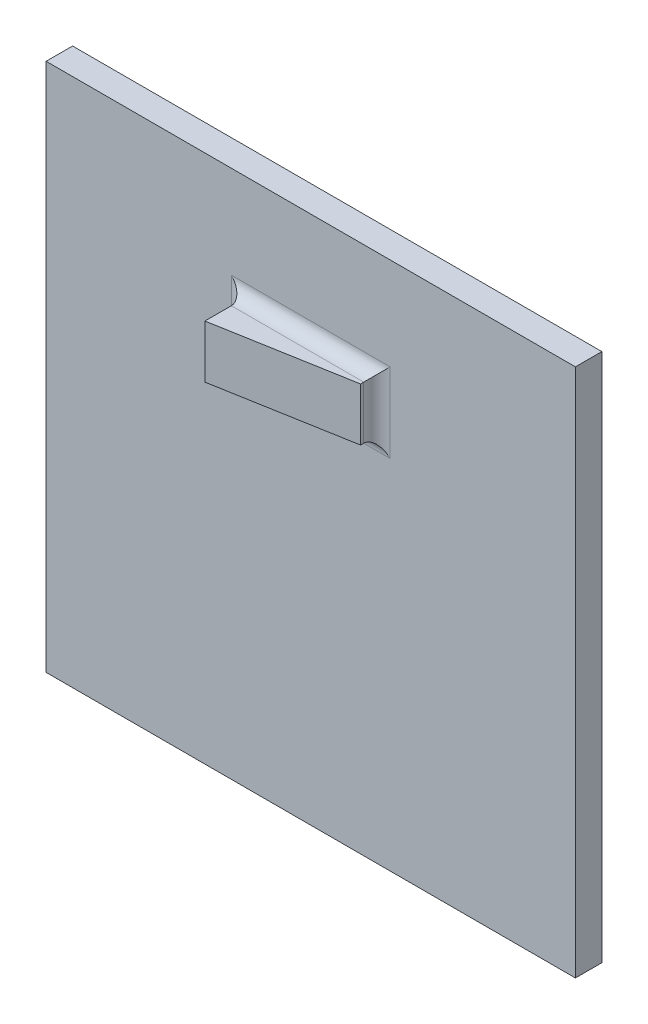
SolidWorks part; units mm, degrees
ref_plane "前视基准面" through (0, 0, 0) normal (0, 0, 1) x (1, 0, 0)
ref_plane "上视基准面" through (0, 0, 0) normal (0, 1, 0) x (1, 0, 0)
ref_plane "右视基准面" through (0, 0, 0) normal (1, 0, 0) x (0, 0, -1)
other "Configuration Table"
sketch "草图1" plane through (0, 0, 0) normal (0, 0, 1) x (1, 0, 0)
  line L1 (-20, 10) -> (20, 10)
  line L2 (-20, 10) -> (-20, -10)
  line L3 (-20, -10) -> (20, -10)
  line L4 (20, 10) -> (20, -10)
  line L5 (-20, 10) -> (20, -10) construction
  line L6 (-20, -10) -> (20, 10) construction
  point P0 (0, 0)
  dimension "D1" = 20
  dimension "D2" = 40
extrude "凸台-拉伸1" add sketch "草图1" along normal blind 2
sketch "草图2" plane through (0, 0, 2) normal (0, 0, 1) x (1, 0, 0)
  line L1 (-5, 2) -> (5, 2)
  line L2 (-5, 2) -> (-5, -2)
  line L3 (-5, -2) -> (5, -2)
  line L4 (5, 2) -> (5, -2)
  line L5 (-5, 2) -> (5, -2) construction
  line L6 (-5, -2) -> (5, 2) construction
  point P0 (0, 0)
  dimension "D1" = 4
  dimension "D2" = 10
extrude "凸台-拉伸2" add sketch "草图2" along normal blind 3
sketch "草图3" plane through (0, -2, 0) normal (0, -1, 0) x (1, 0, 0)
  line L2 (-5, 5) -> (5, 3.2367)
  line L3 (5, 5) -> (5, 2) construction
  line L9 (-5, 2) -> (5, 2)
  line L10 (5, 2) -> (5, 5)
  line L11 (5, 5) -> (-5, 5)
  line L12 (-5, 5) -> (-5, 2)
  line L14 (5, 3.2367) -> (5, 5)
  line L15 (5, 5) -> (-5, 5)
  dimension "D1" = 10
  dimension "D2" = 0
extrude "切除-拉伸1" cut sketch "草图3" against normal up to next
sketch "草图4" plane through (0, -10, 0) normal (0, -1, 0) x (1, 0, 0)
  line L4 (-20, 0) -> (20, 0)
  line L5 (20, 0) -> (20, 2)
  line L6 (20, 2) -> (-20, 2)
  line L7 (-20, 2) -> (-20, 0)
  line L8 (-20, 0) -> (20, 0)
  line L9 (20, 0) -> (20, 2)
  line L10 (20, 2) -> (-20, 2)
  line L11 (-20, 2) -> (-20, 0)
  dimension "D1" = 0
extrude "凸台-拉伸3" add sketch "草图4" along normal blind 20
fillet "圆角1" radius 1 4 edges at (0, -2, 2) (5, 0, 2) (0, 2, 2) (-5, 0, 2)
